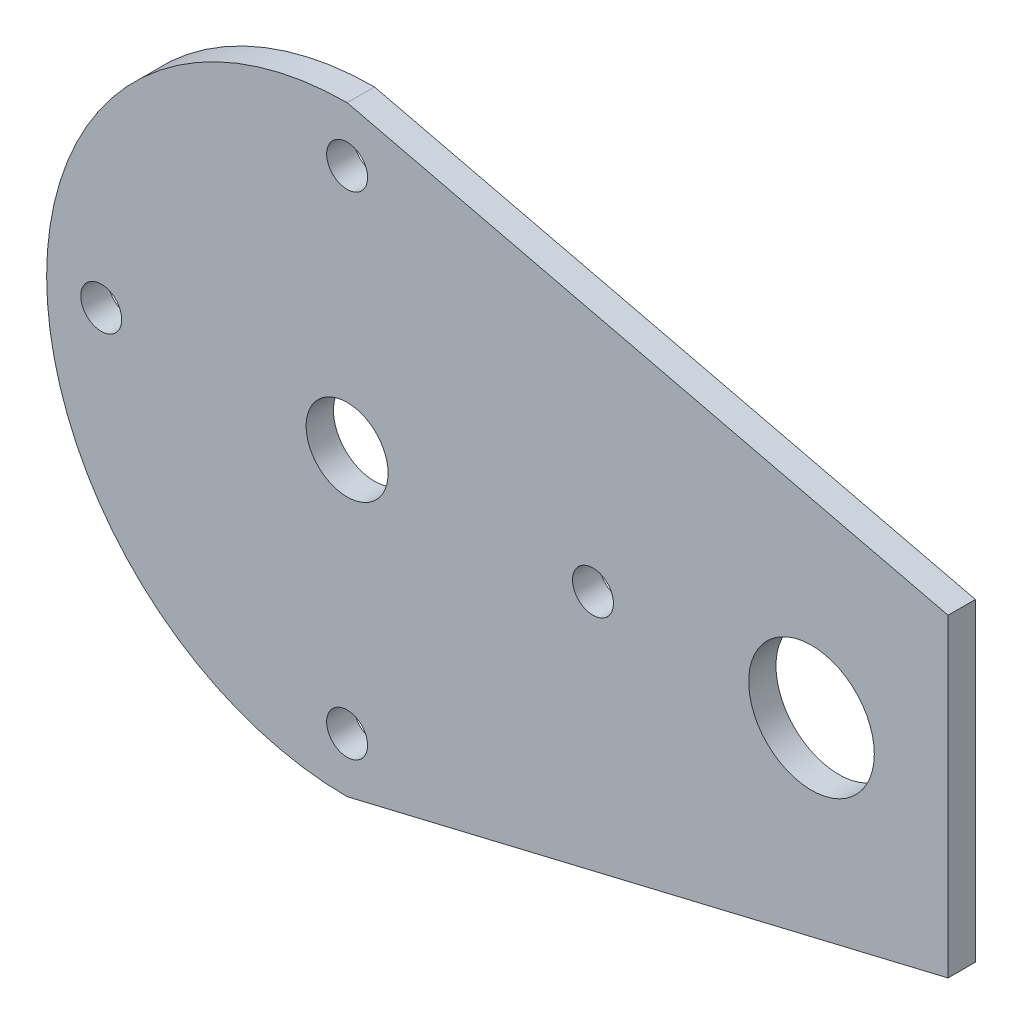
SolidWorks part; units mm, degrees
ref_plane "前视基准面" through (0, 0, 0) normal (0, 0, 1) x (1, 0, 0)
ref_plane "上视基准面" through (0, 0, 0) normal (0, 1, 0) x (1, 0, 0)
ref_plane "右视基准面" through (0, 0, 0) normal (1, 0, 0) x (0, 0, -1)
sketch "草图1" plane through (0, 0, 0) normal (0, 0, 1) x (1, 0, 0)
  line L0 (-38.999, 0) -> (5.001, 0) construction
  line L1 (-38.999, 22.002) -> (5.001, 22.002) construction
  line L6 (-38.999, 22.002) -> (-38.999, -22.002) construction
  line L7 (-38.999, -22.002) -> (5.001, -22.002) construction
  line L11 (5.001, 22.002) -> (5.001, -22.002)
  line L12 (5.001, 22.002) -> (5.001, 1) construction
  line L36 (-9.489, 1) -> (-9.489, -1) construction
  line L40 (-0.509, 1) -> (-0.509, -1) construction
  line L41 (5.001, -1) -> (5.001, -22.002) construction
  line L42 (5.001, 11.501) -> (-38.999, 22.002)
  line L43 (5.001, -11.501) -> (-38.999, -22.002)
  circle A3 centre (-38.999, 0) radius 3
  circle A6 centre (-38.999, 0) radius 11.5 construction
  circle A7 centre (-38.999, -11.5) radius 1.25 construction
  circle A18 centre (-38.999, 0) radius 22.002 construction
  circle A30 centre (-48.9583, -5.75) radius 1.25 construction
  circle A31 centre (-48.9583, 5.75) radius 1.25 construction
  circle A32 centre (-38.999, 11.5) radius 1.25 construction
  circle A33 centre (-29.0397, 5.75) radius 1.25 construction
  circle A34 centre (-29.0397, -5.75) radius 1.25 construction
  arc A35 (-38.999, 22.002) -> (-38.999, -22.002) centre (-38.999, 0) ccw
  circle A37 centre (-4.999, 0) radius 4.6
  circle A40 centre (-38.999, -18.002) radius 1.5
  circle A41 centre (-38.999, 18.002) radius 1.5
  circle A42 centre (-57.001, 0) radius 1.5
  circle A43 centre (-13.999, -5.75) radius 1.5 construction
  circle A44 centre (-13.999, 5.75) radius 1.5 construction
  circle A45 centre (-38.999, 0) radius 18.002 construction
  circle A46 centre (-20.997, 0) radius 1.5
  point P45 (-61.001, 0)
  dimension "D3" = 6
  dimension "D4" = 44
  dimension "D5" = 9.2
  dimension "D6" = 10
  dimension "D7" = 23
  dimension "D8" = 2.5
  dimension "D11" = 4
  dimension "D14" = 25
  dimension "D2" = 44.004
  dimension "D12" = 4
  dimension "D13" = 4
  dimension "D1" = 6
extrude "凸台-拉伸1" add sketch "草图1" along normal blind 2 contours L42 A35 L43 L11 A44 A43 A42 A41 A40 A37 A3
